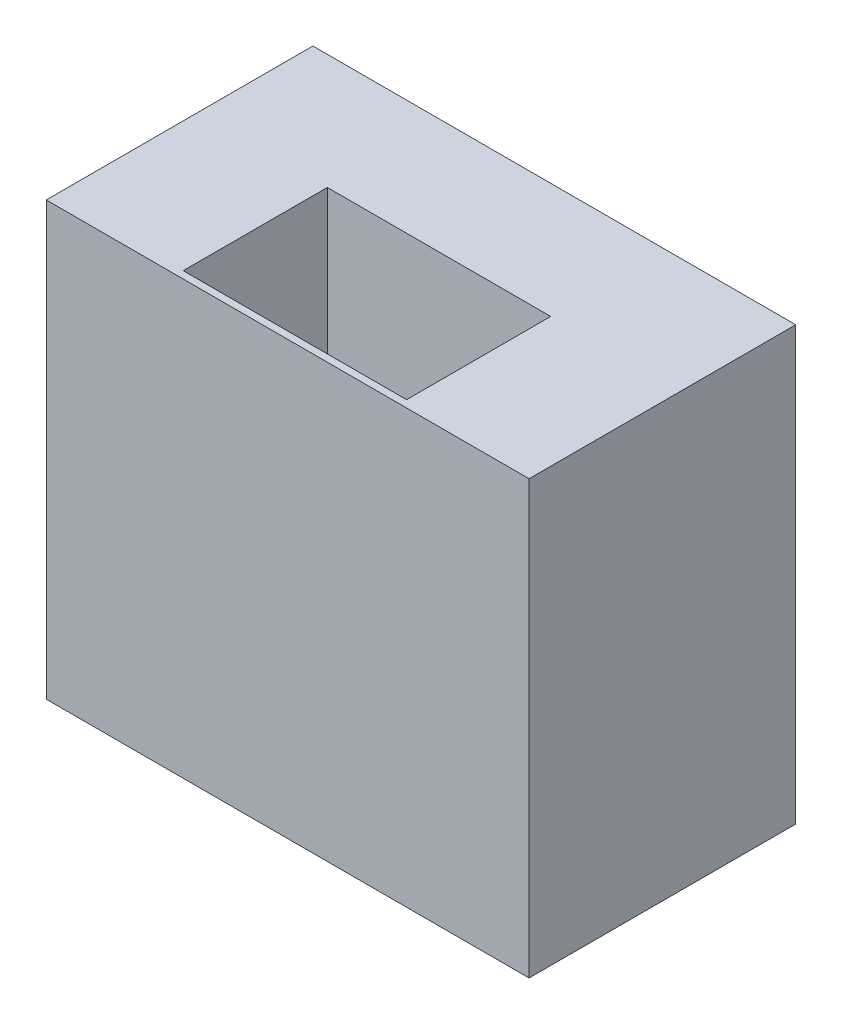
SolidWorks part; units mm, degrees
ref_plane "Front Plane" through (0, 0, 0) normal (0, 0, 1) x (1, 0, 0)
ref_plane "Top Plane" through (0, 0, 0) normal (0, 1, 0) x (1, 0, 0)
ref_plane "Right Plane" through (0, 0, 0) normal (1, 0, 0) x (0, 0, -1)
sketch "Sketch1" plane through (0, 0, 0) normal (0, 1, 0) x (1, 0, 0)
  line L1 (-55.5986, 25.1918) -> (78.4014, 25.1918)
  line L2 (-55.5986, 25.1918) -> (-55.5986, -48.8082)
  line L3 (-55.5986, -48.8082) -> (78.4014, -48.8082)
  line L4 (78.4014, 25.1918) -> (78.4014, -48.8082)
  line L5 (-19.5986, -6.8082) -> (42.4014, -6.8082)
  line L6 (-19.5986, -6.8082) -> (-19.5986, -46.8082)
  line L7 (-19.5986, -46.8082) -> (42.4014, -46.8082)
  line L8 (42.4014, -6.8082) -> (42.4014, -46.8082)
  dimension "D1" = 134
  dimension "D2" = 2
  dimension "D3" = 40
  dimension "D4" = 32
  dimension "D5" = 36
  dimension "D6" = 36
  dimension "D7" = 62
extrude "Boss-Extrude1" add sketch "Sketch1" against normal blind 120
sketch "Sketch2" plane through (0, 0, -25.1918) normal (0, 0, -1) x (-1, 0, 0)
  line L0 (55.5986, -120) -> (55.5986, 0) construction
  line L1 (21.5986, -118) -> (-64.4014, -118)
  line L2 (53.5986, -88) -> (53.5986, -14)
  line L3 (41.5986, -2) -> (-64.4014, -2)
  line L4 (-76.4014, -106) -> (-76.4014, -14)
  line L5 (-78.4014, -120) -> (55.5986, -120) construction
  line L6 (-78.4014, -120) -> (-78.4014, 0) construction
  line L7 (-78.4014, 0) -> (55.5986, 0) construction
  line L11 (-76.4014, -14) -> (-64.4014, -14)
  line L12 (-64.4014, -2) -> (-64.4014, -14)
  line L15 (53.5986, -14) -> (41.5986, -14)
  line L16 (41.5986, -2) -> (41.5986, -14)
  line L23 (-76.4014, -106) -> (-64.4014, -106)
  line L24 (-64.4014, -118) -> (-64.4014, -106)
  line L25 (53.5986, -88) -> (21.5986, -88)
  line L28 (21.5986, -88) -> (21.5986, -118)
  dimension "D1" = 2
  dimension "D2" = 2
  dimension "D3" = 2
  dimension "D4" = 2
  dimension "D5" = 12
  dimension "D6" = 12
  dimension "D7" = 12
  dimension "D8" = 12
  dimension "D11" = 12
  dimension "D12" = 12
  dimension "D13" = 86
  dimension "D14" = 32
extrude "Cut-Extrude1" cut sketch "Sketch2" against normal blind 30
sketch "Sketch4" plane through (0, 0, 4.8082) normal (0, 0, -1) x (-1, 0, 0)
  line L0 (41.5986, -2) -> (-64.4014, -2) construction
  line L1 (21.5986, -2) -> (53.5986, -2)
  line L2 (21.5986, -2) -> (21.5986, -60)
  line L4 (53.5986, -2) -> (53.5986, -60)
  line L6 (53.5986, -88) -> (53.5986, -14) construction
  line L8 (21.5986, -60) -> (53.5986, -60)
  dimension "D1" = 0
  dimension "D2" = 0
  dimension "D4" = 32
  dimension "D5" = 58
extrude "Cut-Extrude2" cut sketch "Sketch4" against normal blind 42
sketch "Sketch5" plane through (0, 0, 4.8082) normal (0, 0, -1) x (-1, 0, 0)
  line L5 (-64.4014, -118) -> (21.5986, -118) construction
  line L6 (-76.4014, -2) -> (-44.4014, -2)
  line L7 (-76.4014, -2) -> (-76.4014, -118)
  line L8 (-76.4014, -118) -> (-44.4014, -118)
  line L9 (-44.4014, -2) -> (-44.4014, -118)
  line L10 (41.5986, -2) -> (-64.4014, -2) construction
  dimension "D1" = 0
  dimension "D2" = 0
  dimension "D3" = 32
extrude "Cut-Extrude3" cut sketch "Sketch5" against normal blind 42
hole_wizard "M2.5 Clearance Hole1" positions "Sketch6" profile "Sketch7" hole size "M2.5" standard "ANSI Metric"
sketch "Sketch6" plane through (0, 0, -25.1918) normal (0, 0, -1) x (-1, 0, 0)
  line L0 (-64.4014, -14) -> (-76.4014, -14) construction
  line L1 (53.5986, -14) -> (41.5986, -14) construction
  line L3 (-76.4014, -106) -> (-64.4014, -106) construction
  line L4 (-64.4014, -2) -> (-64.4014, -14) construction
  line L5 (41.5986, -14) -> (41.5986, -2) construction
  line L6 (55.5986, -120) -> (55.5986, 0) construction
  line L7 (-78.4014, -120) -> (55.5986, -120) construction
  line L8 (-64.4014, -106) -> (-64.4014, -118) construction
  point P0 (-70.4014, -8)
  point P2 (47.5986, -8)
  point P4 (47.5986, -112)
  point P6 (-70.4014, -112)
  dimension "D1" = 6
  dimension "D2" = 6
  dimension "D3" = 6
  dimension "D4" = 6
  dimension "D5" = 6
  dimension "D6" = 8
  dimension "D7" = 8
  dimension "D8" = 6
sketch "Sketch7" plane through (70.4014, -8, -25.1918) normal (1, 0, 0) x (0, 1, 0)
  line L0 (0, 0) -> (0, 14.3866)
  line L1 (0, 14.3866) -> (1.45, 14)
  line L2 (1.45, 14) -> (1.45, 0)
  line L5 (1.45, 0) -> (0, 0)
  line L10 (0, 14.3866) -> (-1.45, 14) construction
  line L11 (0, -6.35) -> (0, 107.95) construction
  dimension "Hole Dia." = 2.9
  dimension "Hole Depth" = 14
  dimension "Drill Angle" = 150.14
sketch "Sketch9" plane through (-55.5986, 0, 0) normal (-1, 0, 0) x (0, 0, 1)
  line L0 (48.8082, -120) -> (48.8082, 0) construction
  line L1 (46.8082, -118) -> (6.8082, -118)
  line L2 (46.8082, -118) -> (46.8082, -62)
  line L3 (46.8082, -62) -> (6.8082, -62)
  line L4 (6.8082, -118) -> (6.8082, -62)
  line L5 (-25.1918, -120) -> (48.8082, -120) construction
  dimension "D1" = 2
  dimension "D2" = 2
  dimension "D3" = 56
  dimension "D4" = 40
extrude "Cut-Extrude9" cut sketch "Sketch9" against normal blind 32
sketch "Sketch10" plane through (0, 0, -25.1918) normal (0, 0, -1) x (-1, 0, 0)
  line L0 (55.5986, -120) -> (55.5986, 0) construction
  line L1 (21.5986, -88) -> (53.5986, -88)
  line L2 (21.5986, -88) -> (21.5986, -118)
  line L3 (21.5986, -118) -> (41.5986, -118)
  line L4 (53.5986, -88) -> (53.5986, -106)
  line L5 (-78.4014, -120) -> (55.5986, -120) construction
  line L6 (53.5986, -106) -> (41.5986, -106)
  line L7 (41.5986, -106) -> (41.5986, -118)
  dimension "D1" = 2
  dimension "D2" = 2
  dimension "D3" = 12
  dimension "D4" = 12
extrude "Cut-Extrude5" cut sketch "Sketch10" against normal blind 20
sketch "Sketch11" plane through (0, 0, -5.1918) normal (0, 0, -1) x (-1, 0, 0)
  line L0 (53.5986, -88) -> (21.5986, -88)
  line L1 (21.5986, -88) -> (21.5986, -118)
  line L2 (21.5986, -118) -> (41.5986, -118)
  line L3 (41.5986, -118) -> (41.5986, -106)
  line L4 (41.5986, -106) -> (53.5986, -106)
  line L5 (53.5986, -88) -> (53.5986, -106)
extrude "Cut-Extrude6" cut sketch "Sketch11" against normal blind 10
sketch "Sketch12" plane through (44.4014, 0, 0) normal (1, 0, 0) x (0, 0, -1)
  line L0 (-4.8082, -118) -> (-4.8082, -2) construction
  line L1 (-4.8082, -2) -> (-9.8082, -2)
  line L2 (-4.8082, -2) -> (-4.8082, -12)
  line L3 (-4.8082, -12) -> (-9.8082, -12)
  line L4 (-9.8082, -2) -> (-9.8082, -12)
  line L7 (-4.8082, -108) -> (-4.8082, -118)
  line L8 (-4.8082, -118) -> (-9.8082, -118)
  line L10 (-46.8082, -2) -> (-4.8082, -2) construction
  line L11 (-9.8082, -118) -> (-9.8082, -108)
  line L12 (-9.8082, -108) -> (-4.8082, -108)
  dimension "D1" = 5
  dimension "D2" = 10
  dimension "D3" = 0
  dimension "D4" = 5
  dimension "D5" = 10
extrude "Boss-Extrude2" add sketch "Sketch12" along normal blind 10
sketch "Sketch13" plane through (0, 0, 4.8082) normal (0, 0, -1) x (-1, 0, 0)
  circle A0 centre (-49.4014, -7) radius 2.5
  circle A1 centre (-49.4014, -113) radius 2.5
  dimension "D1" = 5
  dimension "D2" = 5
extrude "Boss-Extrude4" add sketch "Sketch13" along normal blind 15
sketch "Sketch14" plane through (-21.5986, 0, 0) normal (-1, 0, 0) x (0, 0, 1)
  line L1 (4.8082, -2) -> (9.8082, -2)
  line L2 (4.8082, -2) -> (4.8082, -12)
  line L3 (4.8082, -12) -> (9.8082, -12)
  line L4 (9.8082, -2) -> (9.8082, -12)
  dimension "D1" = 5
  dimension "D2" = 10
extrude "Boss-Extrude3" add sketch "Sketch14" along normal blind 19.99
sketch "Sketch17" plane through (0, 0, 4.8082) normal (0, 0, -1) x (-1, 0, 0)
  line L0 (41.5886, -2) -> (-54.4014, -2) construction
  line L1 (21.5986, -12) -> (31.5986, -12)
  line L2 (21.5986, -12) -> (21.5986, -2)
  line L3 (21.5986, -2) -> (31.5986, -2)
  line L4 (31.5986, -12) -> (31.5986, -2)
  dimension "D1" = 10
extrude "Cut-Extrude10" cut sketch "Sketch17" against normal blind 5
sketch "Sketch18" plane through (0, 0, 4.8082) normal (0, 0, -1) x (-1, 0, 0)
  circle A0 centre (36.5986, -7) radius 2.5
  circle A1 centre (37.3375, -113.739) radius 2.5
  dimension "D1" = 5
  dimension "D2" = 5
extrude "Boss-Extrude5" add sketch "Sketch18" along normal blind 15
sketch "Sketch19" plane through (0, 0, -10.1918) normal (0, 0, -1) x (-1, 0, 0)
  circle A0 centre (-49.4014, -113) radius 2.5
  circle A1 centre (-49.4014, -113) radius 0.75
  circle A2 centre (-49.4014, -7) radius 2.5
  circle A3 centre (-49.4014, -7) radius 0.75
  circle A4 centre (36.5986, -7) radius 2.5
  circle A5 centre (36.5986, -7) radius 0.75
  circle A6 centre (37.3375, -113.739) radius 2.5
  circle A7 centre (37.3375, -113.739) radius 0.75
  dimension "D1" = 1.5
  dimension "D2" = 1.5
  dimension "D3" = 1.5
  dimension "D4" = 1.5
extrude "Cut-Extrude11" cut sketch "Sketch19" against normal blind 5
sketch "Sketch24" plane through (0, 0, 9.8082) normal (0, 0, 1) x (1, 0, 0)
  line L1 (44.4014, -9) -> (50.3212, -9)
  line L4 (44.4014, -7) -> (50.3212, -7)
  line L5 (44.4014, -2) -> (44.4014, -12) construction
  line L6 (50.3212, -7) -> (50.3212, -9)
  line L8 (44.4014, -9) -> (44.4014, -7)
  dimension "D1" = 2
extrude "Boss-Extrude6" add sketch "Sketch24" along normal blind 10
sketch "Sketch25" plane through (0, -9, 0) normal (0, -1, 0) x (1, 0, 0)
  line L0 (50.3212, 9.8082) -> (44.4014, 19.8082)
  line L1 (44.4014, 19.8082) -> (50.3212, 19.8082)
  line L2 (50.3212, 19.8082) -> (50.3212, 9.8082)
extrude "Cut-Extrude14" cut sketch "Sketch25" against normal up to next
sketch "Sketch26" plane through (0, 0, 9.8082) normal (0, 0, 1) x (1, 0, 0)
  line L0 (44.4014, -111.5509) -> (54.4014, -111.5509)
  line L1 (44.4014, -108) -> (44.4014, -118) construction
  line L2 (54.4014, -108) -> (54.4014, -118) construction
  line L3 (54.4014, -111.5509) -> (54.4014, -114.4928)
  line L4 (54.4014, -114.4928) -> (44.4014, -114.4928)
  line L5 (44.4014, -114.4928) -> (44.4014, -111.5509)
extrude "Boss-Extrude7" add sketch "Sketch26" along normal blind 10
sketch "Sketch27" plane through (0, -111.5509, 0) normal (0, 1, 0) x (1, 0, 0)
  line L0 (54.4014, -9.8082) -> (44.4014, -19.8082)
  line L1 (44.4014, -19.8082) -> (54.4014, -19.8082)
  line L2 (54.4014, -19.8082) -> (54.4014, -9.8082)
extrude "Cut-Extrude15" cut sketch "Sketch27" against normal up to next
sketch "Sketch30" plane through (0, 0, 9.8082) normal (0, 0, 1) x (1, 0, 0)
  line L0 (-41.5886, -2) -> (-31.5986, -2) construction
  line L1 (-34.6385, -2) -> (-38.5862, -2)
  line L2 (-34.6385, -2) -> (-34.6385, -12)
  line L3 (-34.6385, -12) -> (-38.5862, -12)
  line L4 (-38.5862, -2) -> (-38.5862, -12)
  line L5 (-41.5886, -12) -> (-31.5986, -12) construction
extrude "Boss-Extrude8" add sketch "Sketch30" along normal blind 10
sketch "Sketch31" plane through (-38.5862, 0, 0) normal (-1, 0, 0) x (0, 0, 1)
  line L0 (19.8082, -2) -> (19.8082, -12)
  line L1 (19.8082, -12) -> (9.8082, -12)
  line L2 (9.8082, -12) -> (19.8082, -2)
extrude "Cut-Extrude18" cut sketch "Sketch31" against normal up to next
sketch "Sketch33" plane through (-55.5986, 0, 0) normal (-1, 0, 0) x (0, 0, 1)
  line L1 (5.8082, -61) -> (47.8082, -61)
  line L2 (5.8082, -61) -> (5.8082, -119)
  line L3 (5.8082, -119) -> (47.8082, -119)
  line L4 (47.8082, -61) -> (47.8082, -119)
  line L5 (6.8082, -62) -> (46.8082, -62)
  line L6 (6.8082, -62) -> (6.8082, -118)
  line L7 (6.8082, -118) -> (46.8082, -118)
  line L8 (46.8082, -62) -> (46.8082, -118)
  dimension "D1" = 1
  dimension "D2" = 1
  dimension "D3" = 1
  dimension "D4" = 1
extrude "Cut-Extrude20" cut sketch "Sketch33" against normal blind 2
sketch "Sketch34" plane through (0, 0, 4.8082) normal (0, 0, -1) x (-1, 0, 0)
  circle A0 centre (37.5308, -66.4348) radius 2
  dimension "D1" = 4
extrude "Cut-Extrude21" cut sketch "Sketch34" against normal up to next
sketch "Sketch36" plane through (0, 0, 46.8082) normal (0, 0, -1) x (-1, 0, 0)
  line L0 (23.5986, -118) -> (53.5986, -118) construction
  line L1 (50.5986, -118) -> (47.5986, -118)
  line L2 (50.5986, -118) -> (50.5986, -114)
  line L3 (50.5986, -114) -> (47.5986, -114)
  line L4 (47.5986, -118) -> (47.5986, -114)
  line L5 (23.5986, -62) -> (53.5986, -62) construction
  line L6 (50.5986, -62) -> (47.5986, -62)
  line L7 (50.5986, -62) -> (50.5986, -66)
  line L8 (50.5986, -66) -> (47.5986, -66)
  line L9 (47.5986, -62) -> (47.5986, -66)
  line L10 (53.5986, -118) -> (53.5986, -62) construction
  dimension "D1" = 3
  dimension "D2" = 3
  dimension "D3" = 3
  dimension "D4" = 3
  dimension "D5" = 4
  dimension "D6" = 4
extrude "Suporte da Tampa - Pilha" add sketch "Sketch36" along normal blind 5
sketch "Sketch37" plane through (0, 0, 6.8082) normal (0, 0, 1) x (1, 0, 0)
  line L0 (-23.5986, -118) -> (-53.5986, -118) construction
  line L1 (-50.5986, -118) -> (-47.5986, -118)
  line L2 (-50.5986, -118) -> (-50.5986, -115)
  line L3 (-50.5986, -115) -> (-47.5986, -115)
  line L4 (-47.5986, -118) -> (-47.5986, -115)
  line L5 (-23.5986, -62) -> (-53.5986, -62) construction
  line L6 (-50.5986, -62) -> (-47.5986, -62)
  line L7 (-50.5986, -62) -> (-50.5986, -65)
  line L8 (-50.5986, -65) -> (-47.5986, -65)
  line L9 (-47.5986, -62) -> (-47.5986, -65)
  line L10 (-53.5986, -62) -> (-53.5986, -118) construction
  point P14 (-50.5986, -116.5)
  dimension "D1" = 3
  dimension "D2" = 3
  dimension "D3" = 3
  dimension "D4" = 3
  dimension "D5" = 3
  dimension "D6" = 3
extrude "Suporte da Tampa 2 - Pilha" add sketch "Sketch37" along normal blind 4
